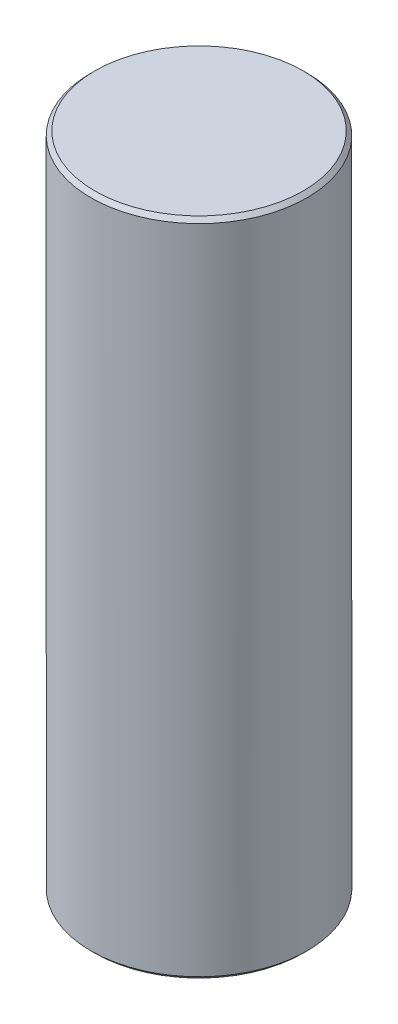
SolidWorks part; units mm, degrees
material "45"
ref_plane "前视基准面" through (0, 0, 0) normal (0, 0, 1) x (1, 0, 0)
ref_plane "上视基准面" through (0, 0, 0) normal (0, 1, 0) x (1, 0, 0)
ref_plane "右视基准面" through (0, 0, 0) normal (1, 0, 0) x (0, 0, -1)
sketch "草图1" plane through (0, 0, 0) normal (0, 1, 0) x (1, 0, 0)
  circle A0 centre (0, 0) radius 27.5
  dimension "D1" = 55
extrude "凸台-拉伸1" add sketch "草图1" along normal blind 168 contours A0
chamfer "倒角1" distance 1 angle 45 2 edges at (0, 0, 27.5) (0, 168, 27.5)
hole_wizard "M12 螺纹孔1" [suppressed] positions "草图2" profile "草图3" tap size "M12" standard "GB"
sketch "草图2" plane through (0, 168, 0) normal (0, 1, 0) x (1, 0, 0)
  point P0 (0, 0)
sketch "草图3" plane through (0, 168, 0) normal (1, 0, 0) x (0, 0, 1)
  line L0 (0, 0) -> (0, 35.8144)
  line L1 (0, 35.8144) -> (5.1, 32.75)
  line L2 (5.1, 32.75) -> (5.1, 0)
  line L5 (5.1, 0) -> (0, 0)
  line L10 (0, 35.8144) -> (-5.1, 32.75) construction
  line L11 (0, -6.35) -> (0, 107.95) construction
  dimension "螺纹孔钻头直径" = 10.2
  dimension "螺纹孔钻头深度" = 32.75
  dimension "导头角度" = 118
cosmetic thread "孔螺蚊线1" [suppressed] parameters "D1"=24, "D2"=12
